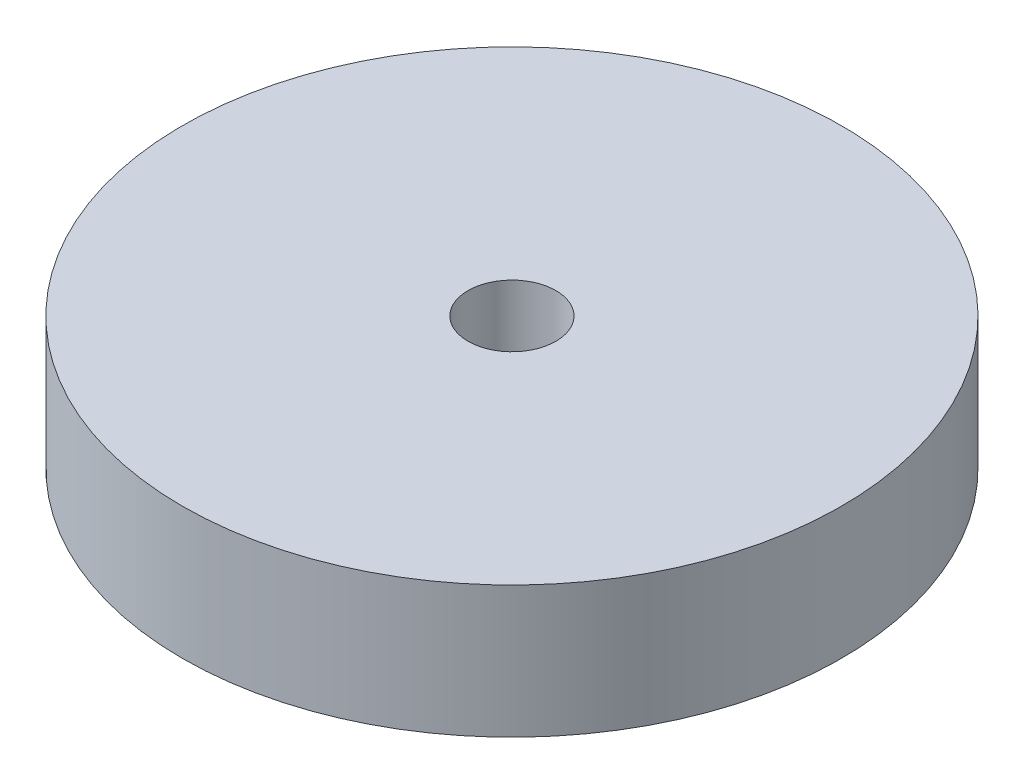
SolidWorks part; units mm, degrees
material "PE High Density"
ref_plane "Front Plane" through (0, 0, 0) normal (0, 0, 1) x (1, 0, 0)
ref_plane "Top Plane" through (0, 0, 0) normal (0, 1, 0) x (1, 0, 0)
ref_plane "Right Plane" through (0, 0, 0) normal (1, 0, 0) x (0, 0, -1)
sketch "Sketch1" plane through (0, 0, 0) normal (0, 1, 0) x (1, 0, 0)
  circle A0 centre (0, 0) radius 375
  dimension "D1" = 750
extrude "Boss-Extrude1" add sketch "Sketch1" along normal blind 150
sketch "Sketch2" plane through (0, 150, 0) normal (0, 1, 0) x (1, 0, 0)
  circle A0 centre (0, 0) radius 50
  dimension "D1" = 100
extrude "Cut-Extrude1" cut sketch "Sketch2" against normal blind 75
scale "Scale1" scale about centroid uniform scaling yes scale factor 0.75
